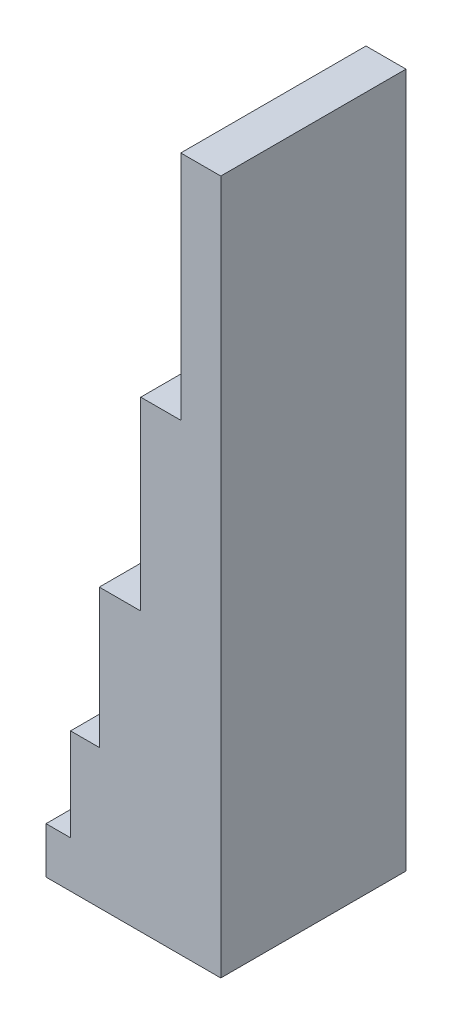
SolidWorks part; units mm, degrees
ref_plane "Front Plane" through (0, 0, 0) normal (0, 0, 1) x (1, 0, 0)
ref_plane "Top Plane" through (0, 0, 0) normal (0, 1, 0) x (1, 0, 0)
ref_plane "Right Plane" through (0, 0, 0) normal (1, 0, 0) x (0, 0, -1)
sketch "Sketch1" plane through (0, 0, 0) normal (0, 0, 1) x (1, 0, 0)
  line L20 (0, 0) -> (0, 2.5)
  line L21 (0, 2.5) -> (1.3235, 2.5)
  line L22 (1.3235, 2.5) -> (1.3235, 7.5)
  line L23 (1.3235, 7.5) -> (2.8771, 7.5)
  line L24 (2.8771, 7.5) -> (2.8771, 15)
  line L25 (2.8771, 15) -> (5.1142, 15)
  line L26 (5.1142, 15) -> (5.1142, 25)
  line L27 (5.1142, 25) -> (7.275, 25)
  line L28 (9.4357, 25) -> (9.4357, 0)
  line L29 (9.4357, 0) -> (0, 0)
  line L30 (7.275, 25) -> (7.275, 37.5)
  line L31 (7.275, 37.5) -> (9.4357, 37.5)
  line L32 (9.4357, 37.5) -> (9.4357, 25)
  dimension "D1" = 10
  dimension "D2" = 7.5
  dimension "D3" = 5
  dimension "D4" = 2.5
  dimension "D5" = 12.5
extrude "Boss-Extrude3" add sketch "Sketch1" along normal blind 10
